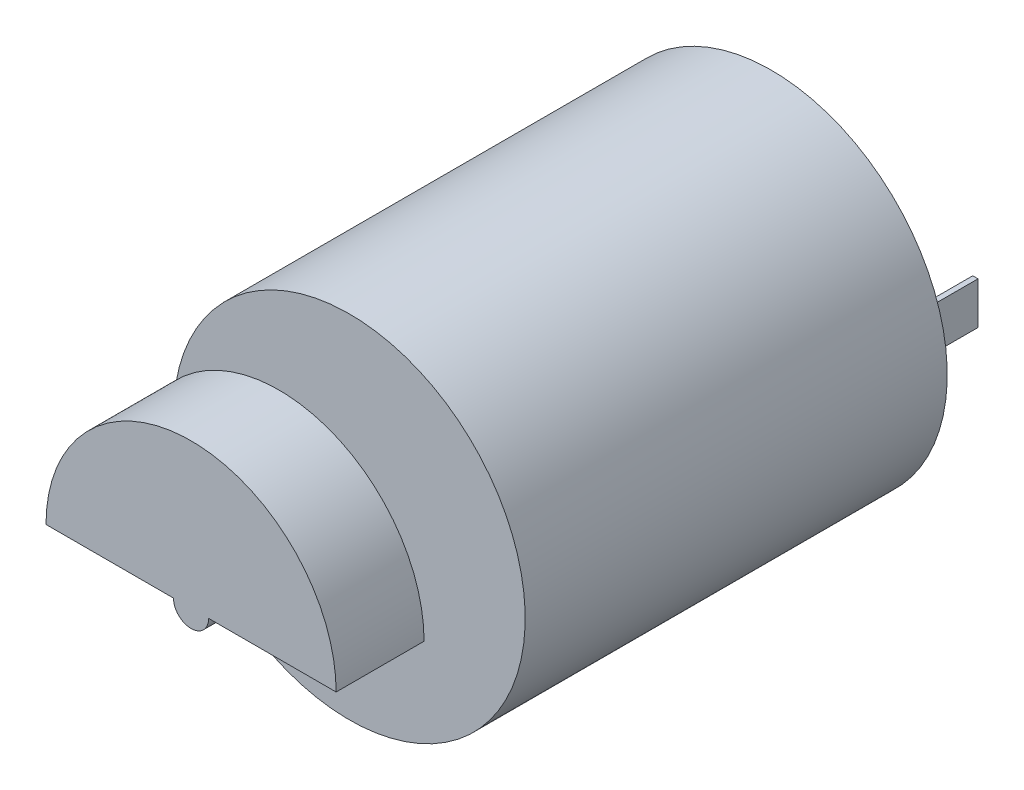
SolidWorks part; units mm, degrees
ref_plane "Front Plane" through (0, 0, 0) normal (0, 0, 1) x (1, 0, 0)
ref_plane "Top Plane" through (0, 0, 0) normal (0, 1, 0) x (1, 0, 0)
ref_plane "Right Plane" through (0, 0, 0) normal (1, 0, 0) x (0, 0, -1)
sketch "Sketch1" plane through (0, 0, 0) normal (0, 0, 1) x (1, 0, 0)
  circle A0 centre (0, 0) radius 12.7
  dimension "D1" = 25.4
extrude "Boss-Extrude1" add sketch "Sketch1" along normal mid plane 30.48
sketch "Sketch2" plane through (0, 0, 15.24) normal (0, 0, 1) x (1, 0, 0)
  circle A0 centre (0, 0) radius 3.048
  dimension "D1" = 6.096
extrude "Boss-Extrude2" add sketch "Sketch2" along normal blind 1.27
sketch "Sketch3" plane through (0, 0, 16.51) normal (0, 0, 1) x (1, 0, 0)
  circle A0 centre (0, 0) radius 1.27
  dimension "D1" = 2.54
extrude "Boss-Extrude3" add sketch "Sketch3" along normal blind 10.16
sketch "Sketch4" plane through (0, 0, 26.67) normal (0, 0, 1) x (1, 0, 0)
  line L0 (13.97, 0) -> (-13.97, 0) construction
  line L1 (-10.4775, 0) -> (10.4775, 0)
  arc A0 (-10.4775, 0) -> (10.4775, 0) centre (0, 0) cw
  dimension "D1" = 10.4775
extrude "Boss-Extrude4" add sketch "Sketch4" against normal blind 6.35
sketch "Sketch5" plane through (0, 0, -15.24) normal (0, 0, -1) x (-1, 0, 0)
  circle A0 centre (0, 0) radius 4.191
  dimension "D1" = 8.382
extrude "Boss-Extrude5" add sketch "Sketch5" along normal blind 2.032
sketch "Sketch6" plane through (0, 0, -15.24) normal (0, 0, -1) x (-1, 0, 0)
  line L0 (13.97, 0) -> (-13.97, 0) construction
  line L1 (-9.3345, 1.524) -> (-8.9535, 1.524)
  line L2 (-9.3345, 1.524) -> (-9.3345, -1.524)
  line L3 (-9.3345, -1.524) -> (-8.9535, -1.524)
  line L4 (-8.9535, 1.524) -> (-8.9535, -1.524)
  line L5 (0, 13.97) -> (0, -13.97) construction
  point P4 (-8.9535, 0)
  dimension "D1" = 3.048
  dimension "D2" = 9.3345
  dimension "D3" = 0.381
extrude "Boss-Extrude6" add sketch "Sketch6" along normal blind 5.588
mirror "Mirror1" about plane through (0, 0, 0) normal (1, 0, 0) of "Boss-Extrude6"
